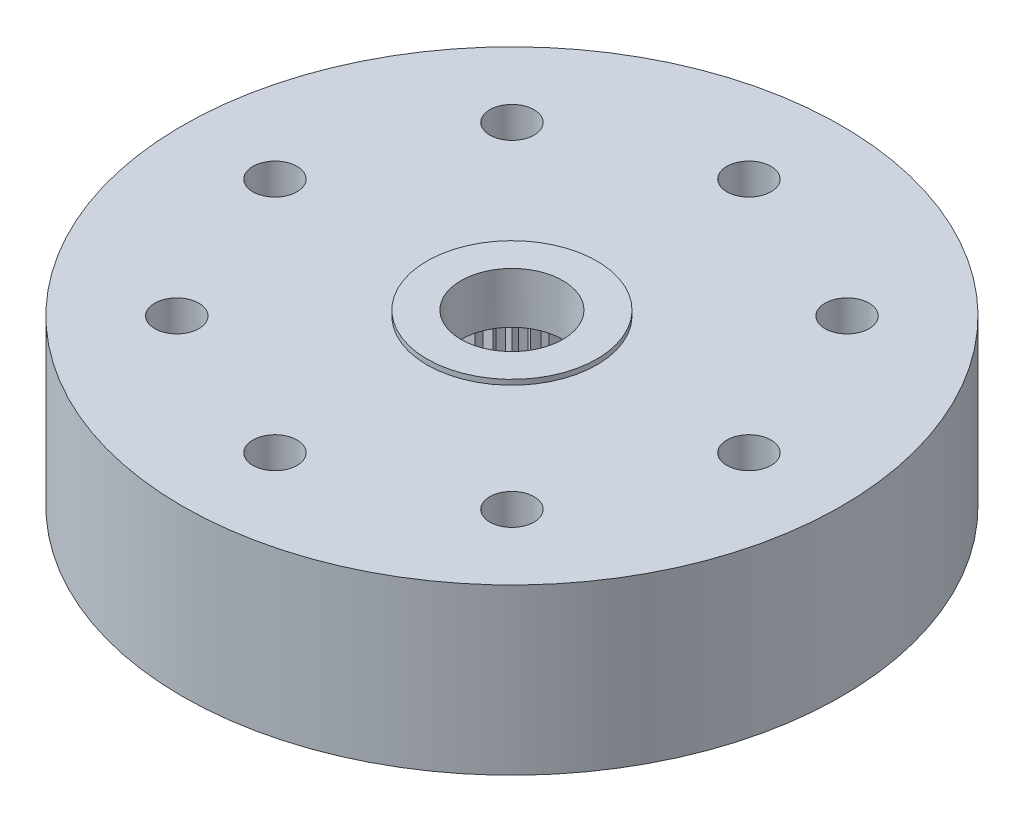
SolidWorks part; units mm, degrees
material "ABS"
ref_plane "Front Plane" through (0, 0, 0) normal (0, 0, 1) x (1, 0, 0)
ref_plane "Top Plane" through (0, 0, 0) normal (0, 1, 0) x (1, 0, 0)
ref_plane "Right Plane" through (0, 0, 0) normal (1, 0, 0) x (0, 0, -1)
sketch "Sketch1" plane through (0, 0, 0) normal (0, 1, 0) x (1, 0, 0)
  circle A0 centre (0, 0) radius 9.7
  dimension "D1" = 19.4
extrude "Boss-Extrude1" add sketch "Sketch1" along normal blind 5 contours A0
sketch "Sketch2" plane through (0, 5, 0) normal (0, 1, 0) x (1, 0, 0)
  circle A0 centre (-6.975, 0) radius 0.65
  circle A1 centre (-4.9321, 4.9321) radius 0.65
  circle A2 centre (0, 6.975) radius 0.65
  circle A3 centre (4.9321, 4.9321) radius 0.65
  circle A4 centre (6.975, 0) radius 0.65
  circle A5 centre (4.9321, -4.9321) radius 0.65
  circle A6 centre (0, -6.975) radius 0.65
  circle A7 centre (-4.9321, -4.9321) radius 0.65
  point P19 (0, 0)
  dimension "D1" = 1.3
  dimension "D2" = 6.975
  dimension "D3" = 0
  dimension "D4" = 8
extrude "Cut-Extrude1" cut sketch "Sketch2" against normal through all both and the other way through all
sketch "Sketch3" plane through (0, 5, 0) normal (0, 1, 0) x (1, 0, 0)
  circle A0 centre (0, 0) radius 1.5
  dimension "D1" = 3
extrude "Cut-Extrude2" cut sketch "Sketch3" against normal through all both and the other way through all
sketch "Sketch4" plane through (0, 5, 0) normal (0, 1, 0) x (1, 0, 0)
  circle A0 centre (0, 0) radius 1.5
  circle A1 centre (0, 0) radius 2.5
  circle A2 centre (0, 0) radius 9.7
  circle M2 centre (-6.975, 0) radius 0.65
  circle M3 centre (-4.9321, 4.9321) radius 0.65
  circle M4 centre (0, 6.975) radius 0.65
  circle M5 centre (4.9321, 4.9321) radius 0.65
  circle M6 centre (6.975, 0) radius 0.65
  circle M7 centre (4.9321, -4.9321) radius 0.65
  circle M8 centre (0, -6.975) radius 0.65
  circle M9 centre (-4.9321, -4.9321) radius 0.65
  circle M10 centre (0, 0) radius 9.7
  dimension "D1" = 5
extrude "Cut-Extrude3" cut sketch "Sketch4" against normal blind 0.15 contours A1 M10 M2 M4 M6 M8 M9 M7 M5 M3
sketch "Sketch5" plane through (0, 0, 0) normal (0, -1, 0) x (1, 0, 0)
  line L0 (-0.6027, -2.9388) -> (-0.3911, -2.4692)
  line L1 (-0.3911, -2.4692) -> (-0.335, -2.9812)
  line L2 (-0.1355, -2.9969) -> (0, -2.5)
  line L3 (0, -2.5) -> (0.1355, -2.9969)
  line L4 (0.335, -2.9812) -> (0.3911, -2.4692)
  line L5 (0.3911, -2.4692) -> (0.6027, -2.9388)
  line L6 (0.7972, -2.8921) -> (0.7725, -2.3776)
  line L7 (0.7725, -2.3776) -> (1.055, -2.8084)
  line L8 (1.2398, -2.7318) -> (1.135, -2.2275)
  line L9 (1.135, -2.2275) -> (1.4813, -2.6088)
  line L10 (1.6519, -2.5042) -> (1.4695, -2.0225)
  line L11 (1.4695, -2.0225) -> (1.8712, -2.3449)
  line L12 (2.0233, -2.215) -> (1.7678, -1.7678)
  line L13 (1.7678, -1.7678) -> (2.215, -2.0233)
  line L14 (2.3449, -1.8712) -> (2.0225, -1.4695)
  line L15 (2.0225, -1.4695) -> (2.5042, -1.6519)
  line L16 (2.6088, -1.4813) -> (2.2275, -1.135)
  line L17 (2.2275, -1.135) -> (2.7318, -1.2398)
  line L18 (2.8084, -1.055) -> (2.3776, -0.7725)
  line L19 (2.3776, -0.7725) -> (2.8921, -0.7972)
  line L20 (2.9388, -0.6027) -> (2.4692, -0.3911)
  line L21 (2.4692, -0.3911) -> (2.9812, -0.335)
  line L22 (2.9969, -0.1355) -> (2.5, 0)
  line L23 (2.5, 0) -> (2.9969, 0.1355)
  line L24 (2.9812, 0.335) -> (2.4692, 0.3911)
  line L25 (2.4692, 0.3911) -> (2.9388, 0.6027)
  line L26 (2.8921, 0.7972) -> (2.3776, 0.7725)
  line L27 (2.3776, 0.7725) -> (2.8084, 1.055)
  line L28 (2.7318, 1.2398) -> (2.2275, 1.135)
  line L29 (2.2275, 1.135) -> (2.6088, 1.4813)
  line L30 (2.5042, 1.6519) -> (2.0225, 1.4695)
  line L31 (2.0225, 1.4695) -> (2.3449, 1.8712)
  line L32 (2.215, 2.0233) -> (1.7678, 1.7678)
  line L33 (1.7678, 1.7678) -> (2.0233, 2.215)
  line L34 (1.8712, 2.3449) -> (1.4695, 2.0225)
  line L35 (1.4695, 2.0225) -> (1.6519, 2.5042)
  line L36 (1.4813, 2.6088) -> (1.135, 2.2275)
  line L37 (1.135, 2.2275) -> (1.2398, 2.7318)
  line L38 (1.055, 2.8084) -> (0.7725, 2.3776)
  line L39 (0.7725, 2.3776) -> (0.7972, 2.8921)
  line L40 (0.6027, 2.9388) -> (0.3911, 2.4692)
  line L41 (0.3911, 2.4692) -> (0.335, 2.9812)
  line L42 (0.1355, 2.9969) -> (0, 2.5)
  line L43 (0, 2.5) -> (-0.1355, 2.9969)
  line L44 (-0.335, 2.9812) -> (-0.3911, 2.4692)
  line L45 (-0.3911, 2.4692) -> (-0.6027, 2.9388)
  line L46 (-0.7972, 2.8921) -> (-0.7725, 2.3776)
  line L47 (-0.7725, 2.3776) -> (-1.055, 2.8084)
  line L48 (-1.2398, 2.7318) -> (-1.135, 2.2275)
  line L49 (-1.135, 2.2275) -> (-1.4813, 2.6088)
  line L50 (-1.6519, 2.5042) -> (-1.4695, 2.0225)
  line L51 (-1.4695, 2.0225) -> (-1.8712, 2.3449)
  line L52 (-2.0233, 2.215) -> (-1.7678, 1.7678)
  line L53 (-1.7678, 1.7678) -> (-2.215, 2.0233)
  line L54 (-2.3449, 1.8712) -> (-2.0225, 1.4695)
  line L55 (-2.0225, 1.4695) -> (-2.5042, 1.6519)
  line L56 (-2.6088, 1.4813) -> (-2.2275, 1.135)
  line L57 (-2.2275, 1.135) -> (-2.7318, 1.2398)
  line L58 (-2.8084, 1.055) -> (-2.3776, 0.7725)
  line L59 (-2.3776, 0.7725) -> (-2.8921, 0.7972)
  line L60 (-2.9388, 0.6027) -> (-2.4692, 0.3911)
  line L61 (-2.4692, 0.3911) -> (-2.9812, 0.335)
  line L62 (-2.9969, 0.1355) -> (-2.5, 0)
  line L63 (-2.5, 0) -> (-2.9969, -0.1355)
  line L64 (-2.9812, -0.335) -> (-2.4692, -0.3911)
  line L65 (-2.4692, -0.3911) -> (-2.9388, -0.6027)
  line L66 (-2.8921, -0.7972) -> (-2.3776, -0.7725)
  line L67 (-2.3776, -0.7725) -> (-2.8084, -1.055)
  line L68 (-2.7318, -1.2398) -> (-2.2275, -1.135)
  line L69 (-2.2275, -1.135) -> (-2.6088, -1.4813)
  line L70 (-2.5042, -1.6519) -> (-2.0225, -1.4695)
  line L71 (-2.0225, -1.4695) -> (-2.3449, -1.8712)
  line L72 (-2.215, -2.0233) -> (-1.7678, -1.7678)
  line L73 (-1.7678, -1.7678) -> (-2.0233, -2.215)
  line L74 (-1.8712, -2.3449) -> (-1.4695, -2.0225)
  line L75 (-1.4695, -2.0225) -> (-1.6519, -2.5042)
  line L76 (-1.4813, -2.6088) -> (-1.135, -2.2275)
  line L77 (-1.135, -2.2275) -> (-1.2398, -2.7318)
  line L78 (-1.055, -2.8084) -> (-0.7725, -2.3776)
  line L79 (-0.7725, -2.3776) -> (-0.7972, -2.8921)
  arc A0 (-0.335, -2.9812) -> (-0.1355, -2.9969) centre (0, 0) ccw
  arc A1 (0.1355, -2.9969) -> (0.335, -2.9812) centre (0, 0) ccw
  arc A2 (0.6027, -2.9388) -> (0.7972, -2.8921) centre (0, 0) ccw
  arc A3 (1.055, -2.8084) -> (1.2398, -2.7318) centre (0, 0) ccw
  arc A4 (1.4813, -2.6088) -> (1.6519, -2.5042) centre (0, 0) ccw
  arc A5 (1.8712, -2.3449) -> (2.0233, -2.215) centre (0, 0) ccw
  arc A6 (2.215, -2.0233) -> (2.3449, -1.8712) centre (0, 0) ccw
  arc A7 (2.5042, -1.6519) -> (2.6088, -1.4813) centre (0, 0) ccw
  arc A8 (2.7318, -1.2398) -> (2.8084, -1.055) centre (0, 0) ccw
  arc A9 (2.8921, -0.7972) -> (2.9388, -0.6027) centre (0, 0) ccw
  arc A10 (2.9812, -0.335) -> (2.9969, -0.1355) centre (0, 0) ccw
  arc A11 (2.9969, 0.1355) -> (2.9812, 0.335) centre (0, 0) ccw
  arc A12 (2.9388, 0.6027) -> (2.8921, 0.7972) centre (0, 0) ccw
  arc A13 (2.8084, 1.055) -> (2.7318, 1.2398) centre (0, 0) ccw
  arc A14 (2.6088, 1.4813) -> (2.5042, 1.6519) centre (0, 0) ccw
  arc A15 (2.3449, 1.8712) -> (2.215, 2.0233) centre (0, 0) ccw
  arc A16 (2.0233, 2.215) -> (1.8712, 2.3449) centre (0, 0) ccw
  arc A17 (1.6519, 2.5042) -> (1.4813, 2.6088) centre (0, 0) ccw
  arc A18 (1.2398, 2.7318) -> (1.055, 2.8084) centre (0, 0) ccw
  arc A19 (0.7972, 2.8921) -> (0.6027, 2.9388) centre (0, 0) ccw
  arc A20 (0.335, 2.9812) -> (0.1355, 2.9969) centre (0, 0) ccw
  arc A21 (-0.1355, 2.9969) -> (-0.335, 2.9812) centre (0, 0) ccw
  arc A22 (-0.6027, 2.9388) -> (-0.7972, 2.8921) centre (0, 0) ccw
  arc A23 (-1.055, 2.8084) -> (-1.2398, 2.7318) centre (0, 0) ccw
  arc A24 (-1.4813, 2.6088) -> (-1.6519, 2.5042) centre (0, 0) ccw
  arc A25 (-1.8712, 2.3449) -> (-2.0233, 2.215) centre (0, 0) ccw
  arc A26 (-2.215, 2.0233) -> (-2.3449, 1.8712) centre (0, 0) ccw
  arc A27 (-2.5042, 1.6519) -> (-2.6088, 1.4813) centre (0, 0) ccw
  arc A28 (-2.7318, 1.2398) -> (-2.8084, 1.055) centre (0, 0) ccw
  arc A29 (-2.8921, 0.7972) -> (-2.9388, 0.6027) centre (0, 0) ccw
  arc A30 (-2.9812, 0.335) -> (-2.9969, 0.1355) centre (0, 0) ccw
  arc A31 (-2.9969, -0.1355) -> (-2.9812, -0.335) centre (0, 0) ccw
  arc A32 (-2.9388, -0.6027) -> (-2.8921, -0.7972) centre (0, 0) ccw
  arc A33 (-2.8084, -1.055) -> (-2.7318, -1.2398) centre (0, 0) ccw
  arc A34 (-2.6088, -1.4813) -> (-2.5042, -1.6519) centre (0, 0) ccw
  arc A35 (-2.3449, -1.8712) -> (-2.215, -2.0233) centre (0, 0) ccw
  arc A36 (-2.0233, -2.215) -> (-1.8712, -2.3449) centre (0, 0) ccw
  arc A37 (-1.6519, -2.5042) -> (-1.4813, -2.6088) centre (0, 0) ccw
  arc A38 (-1.2398, -2.7318) -> (-1.055, -2.8084) centre (0, 0) ccw
  arc A39 (-0.7972, -2.8921) -> (-0.6027, -2.9388) centre (0, 0) ccw
extrude "Cut-Extrude4" cut sketch "Sketch5" against normal blind 3.5
